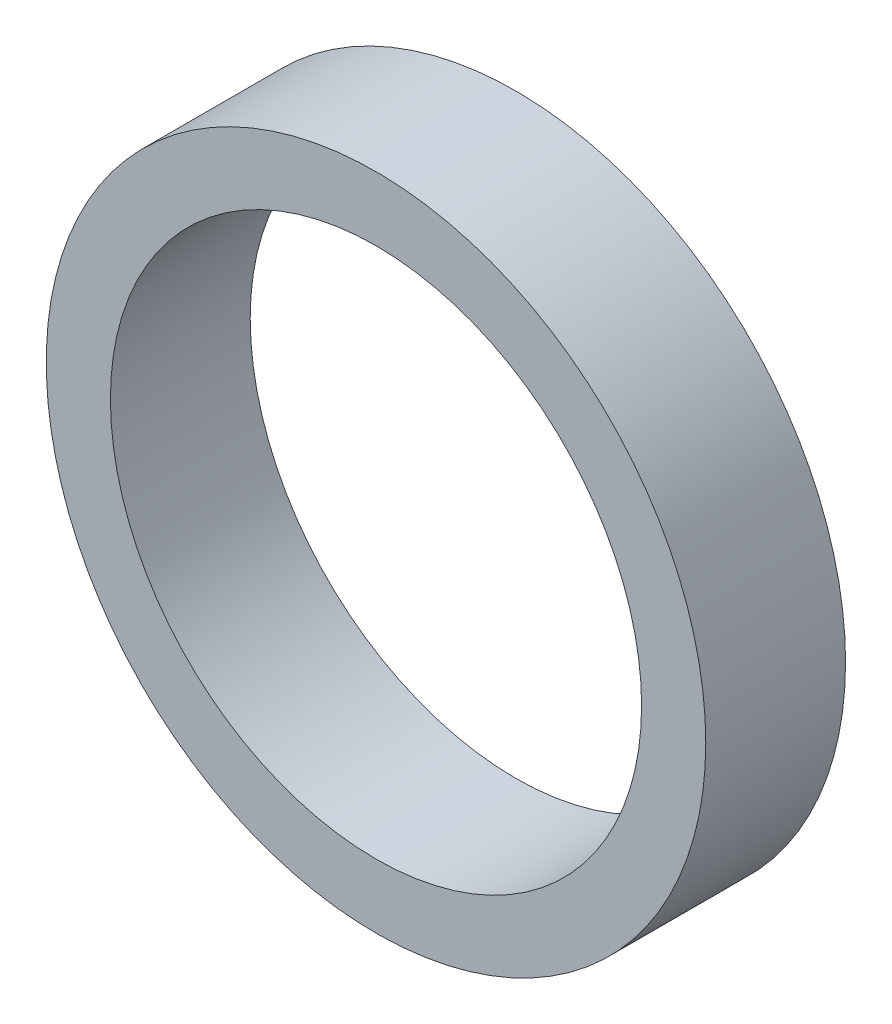
SolidWorks part; units mm, degrees
ref_plane "Plano frontal" through (0, 0, 0) normal (0, 0, 1) x (1, 0, 0)
ref_plane "Plano superior" through (0, 0, 0) normal (0, 1, 0) x (1, 0, 0)
ref_plane "Plano direito" through (0, 0, 0) normal (1, 0, 0) x (0, 0, -1)
sketch "Sketch1" plane through (0, 0, 0) normal (0, 0, 1) x (1, 0, 0)
  circle A0 centre (0, 0) radius 23.59
  circle A1 centre (0, 0) radius 19
  dimension "D1" = 38
  dimension "D2" = 47.18
extrude "Boss-Extrude1" add sketch "Sketch1" along normal blind 10
